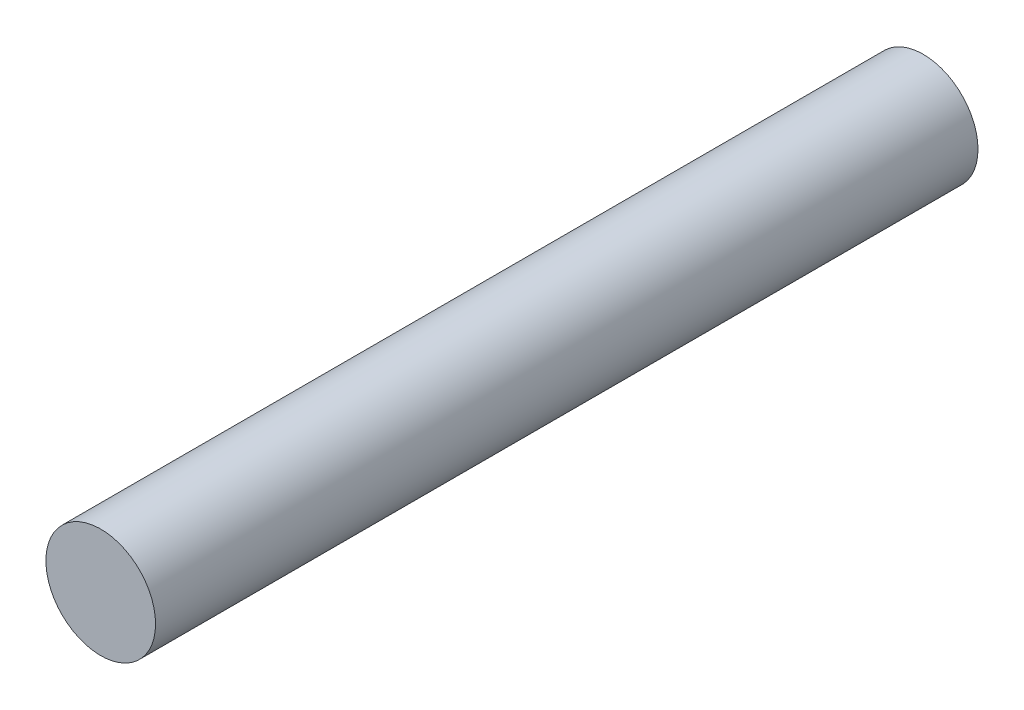
SolidWorks part; units mm, degrees
ref_plane "Front Plane" through (0, 0, 0) normal (0, 0, 1) x (1, 0, 0)
ref_plane "Top Plane" through (0, 0, 0) normal (0, 1, 0) x (1, 0, 0)
ref_plane "Right Plane" through (0, 0, 0) normal (1, 0, 0) x (0, 0, -1)
sketch "Sketch1" plane through (0, 0, 0) normal (0, 0, 1) x (1, 0, 0)
  circle A0 centre (0, 0) radius 5
  dimension "D1" = 10
extrude "Boss-Extrude1" add sketch "Sketch1" along normal blind 75
